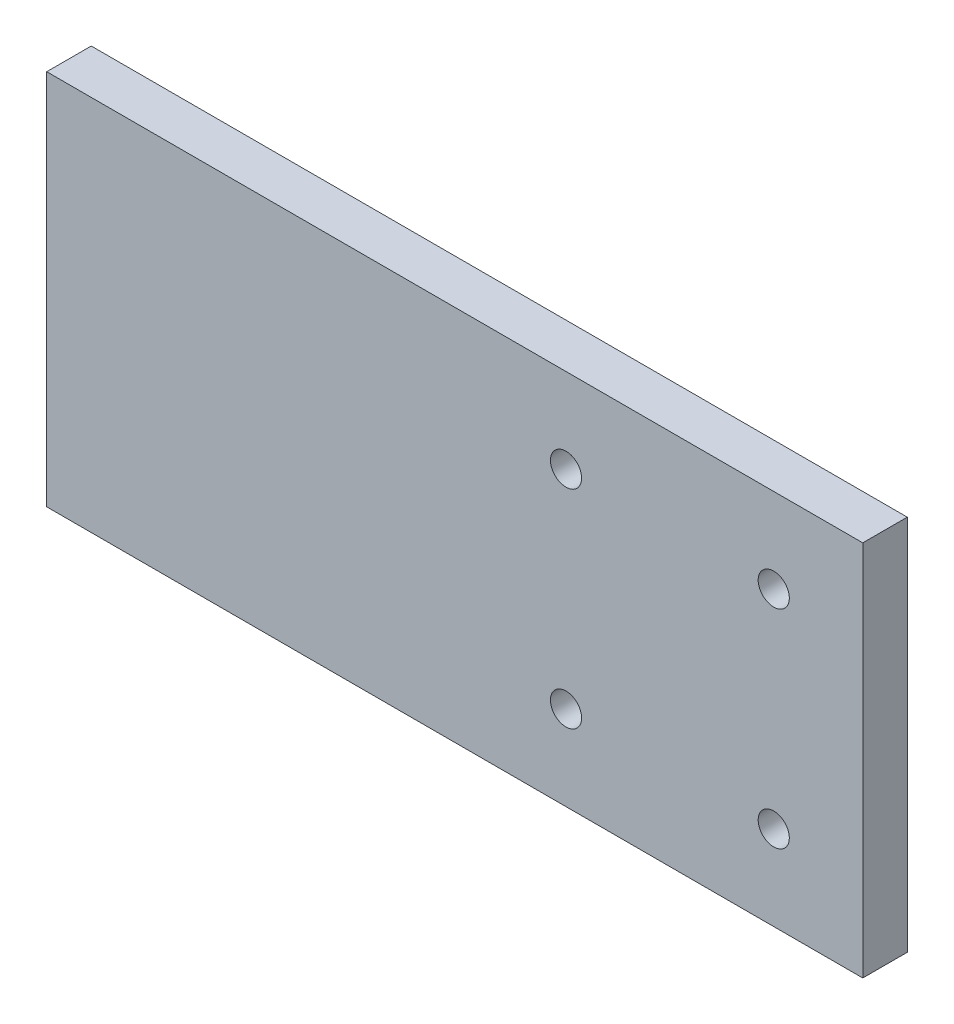
SolidWorks part; units mm, degrees
ref_plane "Front Plane" through (0, 0, 0) normal (0, 0, 1) x (1, 0, 0)
ref_plane "Top Plane" through (0, 0, 0) normal (0, 1, 0) x (1, 0, 0)
ref_plane "Right Plane" through (0, 0, 0) normal (1, 0, 0) x (0, 0, -1)
sketch "Sketch1" plane through (0, 0, 0) normal (0, 0, 1) x (1, 0, 0)
  line L1 (0, 0) -> (110, 0)
  line L2 (0, 0) -> (0, 50.8)
  line L3 (0, 50.8) -> (110, 50.8)
  line L4 (110, 0) -> (110, 50.8)
  circle A0 centre (98, 39.4) radius 2.1
  circle A1 centre (98, 11.4) radius 2.1
  circle A2 centre (70, 39.4) radius 2.1
  circle A3 centre (70, 11.4) radius 2.1
  dimension "D4" = 4.2
  dimension "D5" = 4.2
  dimension "D8" = 4.2
  dimension "D9" = 4.2
  dimension "D1" = 50.8
  dimension "D2" = 110
  dimension "D3" = 12
  dimension "D6" = 28
  dimension "D7" = 11.4
  dimension "D10" = 28
  dimension "D11" = 11.4
  dimension "D12" = 28
extrude "Boss-Extrude1" add sketch "Sketch1" along normal blind 6
equation "\"D5@Sketch1\"=\"D4@Sketch1\""
equation "\"D8@Sketch1\"=\"D4@Sketch1\""
equation "\"D9@Sketch1\"=\"D4@Sketch1\""
equation "\"D10@Sketch1\"=\"D6@Sketch1\""
equation "\"D11@Sketch1\"=\"D7@Sketch1\""
